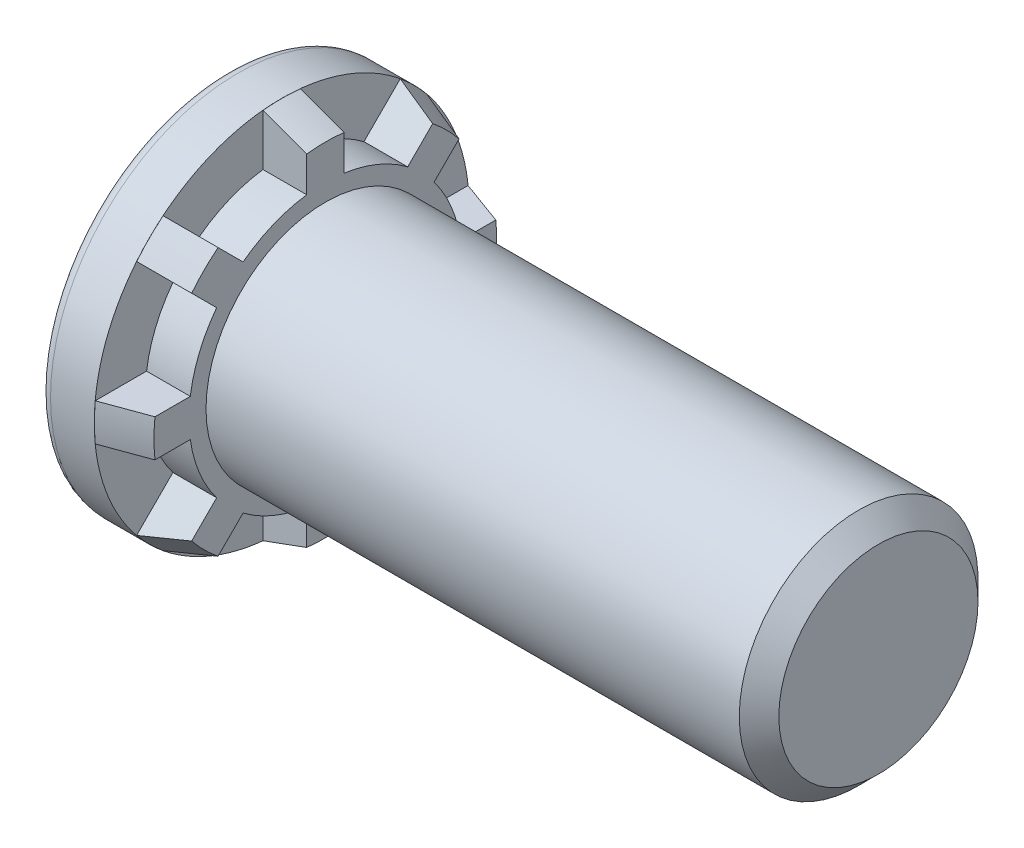
SolidWorks part; units mm, degrees
revolve "BaseBody" add sketch "BodySke" angle 360 about L6
sketch "BodySke" plane through (0, 0, 0) normal (0, 0, 1) x (1, 0, 0)
  line L0 (-2.29, 7.392) -> (-2.29, 0)
  line L1 (1.832, 7.1816) -> (1.832, 5)
  line L2 (0.0025, 7.8475) -> (1.832, 7.1816)
  line L3 (1.832, 5) -> (24.172, 5)
  line L4 (25, 4.172) -> (25, 0)
  line L5 (25, 0) -> (-2.29, 0)
  line L6 (0, 0) -> (50.554, 0) construction
  line L8 (25, 4.172) -> (24.172, 5)
  line L9 (-1.832, 7.85) -> (0, 7.85)
  line L10 (0.0025, 7.8475) -> (0, 7.8475)
  line L11 (1.5, 19.05) -> (1.5, -3.175) construction
  line L12 (0, 7.8475) -> (0, 7.85)
  arc A0 (-2.29, 7.392) -> (-1.832, 7.85) centre (-1.832, 7.392) cw
  dimension "Fillet_rad" = 0.458
  dimension "Body_ch_ang" = 45
  dimension "Minor_dia" = 8.344
  dimension "Diameter" = 10
  dimension "T_dim" = 2.29
  dimension "H_dia" = 15.7
  dimension "D2" = 0.0025
  dimension "D3" = 0.0025
  dimension "Length" = 25
  dimension "Advance" = 1.5
  dimension "D1" = 20
  dimension "Clinch_ht" = 1.832
cosmetic thread "ThreadCosmetic" [suppressed] parameters "Thread_length"=20.9, "Thread_minor"=8.344
ref_plane "Plane1" through (0, 0, 0) normal (0, 0, 1) x (1, 0, 0)
ref_plane "Plane2" through (0, 0, 0) normal (0, 1, 0) x (1, 0, 0)
ref_plane "Plane3" through (0, 0, 0) normal (1, 0, 0) x (0, 0, -1)
sketch "ThdSchSke" plane through (0, 0, 0) normal (0, 0, 1) x (1, 0, 0)
  line L0 (4.1, -4.172) -> (3.5202, -5)
  line L1 (4.1, -4.172) -> (4.6798, -5)
  line L2 (4.6798, -5) -> (4.6798, -6.25)
  line L3 (-3.175, 0) -> (5.1513, 0) construction
  line L4 (0, -7.85) -> (0, 7.85) construction
  line L5 (4.6798, -6.25) -> (3.5202, -6.25)
  line L6 (3.5202, -6.25) -> (3.5202, -5)
  dimension "Diameter" = 10
  dimension "Thread_minor" = 8.344
  dimension "Start" = 4.1
revolve "ThreadSchematic" [suppressed] cut sketch "ThdSchSke" angle 360 about L3
pattern_linear "ThdSchPat" [suppressed]
sketch "RibCutSke" plane through (1.832, 1.7944, -0.091) normal (1, 0, 0) x (0, 0, -1)
  line L0 (0.6912, 3.8643) -> (0.6912, 6.0165)
  line L1 (3.3573, 2.76) -> (4.8791, 4.2818)
  line L2 (0.6912, 3.144) -> (0.6912, 2.4006) construction
  line L3 (-0.091, -1.7944) -> (-0.091, 5.0239) construction
  line L4 (-0.091, -1.7944) -> (0.6912, 3.144) construction
  line L5 (-0.091, -1.7944) -> (2.848, 2.2507) construction
  line L6 (2.848, 2.2507) -> (2.3273, 1.73) construction
  arc A1 (3.3573, 2.76) -> (0.6912, 3.8643) centre (-0.091, -1.7944) ccw
  arc A2 (4.8791, 4.2818) -> (0.6912, 6.0165) centre (-0.091, -1.7944) ccw
  circle A3 centre (-0.091, -1.7944) radius 7.1816 construction
  circle A4 centre (-0.091, -1.7944) radius 5 construction
  dimension "Rib_root_half_angle" = 9
  dimension "Rib_root_gap_angle" = 27
  dimension "Angle" = 45
extrude "RibCut" cut sketch "RibCutSke" against normal blind 1.832
pattern_circular "RibCutsPat" count 8 every 45 about axis through (0, 0, 0) along (1, 0, 0) of "RibCut"
equation "' \"Length@BodySke\" = 25"
equation "' \"H_dia@BodySke\" = 15.7"
equation "' \"Start@ThdSchSke\" = 4.1"
equation "' \"T_dim@BodySke\" = 2.29"
equation "' \"Diameter@BodySke\" = 10"
equation "' \"Minor_dia@BodySke\" = 8.344"
equation "' \"Advance@BodySke\" = 1.5"
equation "\"Fillet_rad@BodySke\" =  \"T_dim@BodySke\" * 0.2"
equation "\"Clinch_ht@BodySke\" = \"T_dim@BodySke\" * 0.8"
equation "\"Num_ribs@RibCutsPat\" = 8"
equation "\"Angle@RibCutSke\" =\"Angle@RibCutsPat\""
equation "\"Rib_root_half_angle@RibCutSke\" = \"Angle@RibCutSke\" / 5"
equation "\"Rib_root_gap_angle@RibCutSke\" = \"Angle@RibCutSke\" - (2 * \"Rib_root_half_angle@RibCutSke\" )"
equation "\"Rib_root_dia@RibCutSke\" = \"Diameter@BodySke\""
equation "\"Inner_dia@RibCutSke\" = \"Diameter@BodySke\" + ( \"H_dia@BodySke\" - \"Diameter@BodySke\" ) / 4"
equation "\"Outer_dia@RibCutSke\" = \"H_dia@BodySke\""
equation "\"Depth@RibCut\" = \"Clinch_ht@BodySke\""
equation "\"Thread_length@ThreadCosmetic\" = \"Length@BodySke\" - \"Start@ThdSchSke\""
equation "\"Thread_minor@ThreadCosmetic\" = \"Minor_dia@BodySke\""
equation "\"Thread_minor@ThdSchSke\" = \"Minor_dia@BodySke\""
equation "\"Diameter@ThdSchSke\" = \"Diameter@BodySke\""
equation "\"Overcut@ThdSchSke\" = \"Diameter@BodySke\" * 1.25"
equation "\"Num_threads@ThdSchPat\" = int( \"Thread_length@ThreadCosmetic\" / \"Advance@BodySke\" + 0.999 )  + 1"
equation "\"Advance@ThdSchPat\" = \"Thread_length@ThreadCosmetic\" /  (\"Num_threads@ThdSchPat\" - 1) 'relax it"
equation "\"Num_threads@ThdSchPat\" = \"Num_threads@ThdSchPat\" - sgn( \"Num_threads@ThdSchPat\" - 1) '---chamfered tips only---"
